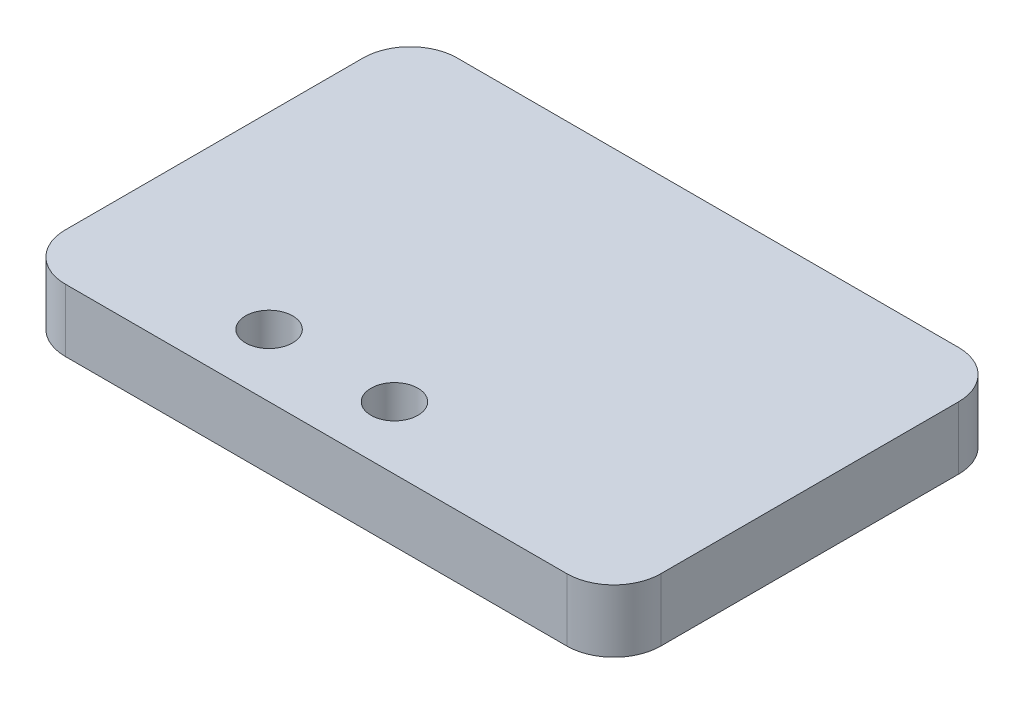
SolidWorks part; units mm, degrees
material "Thornel Mat VMA"
ref_plane "前视基准面" through (0, 0, 0) normal (0, 0, 1) x (1, 0, 0)
ref_plane "上视基准面" through (0, 0, 0) normal (0, 1, 0) x (1, 0, 0)
ref_plane "右视基准面" through (0, 0, 0) normal (1, 0, 0) x (0, 0, -1)
other "Configuration Table"
sketch "草图1" plane through (0, 0, 0) normal (0, 1, 0) x (1, 0, 0)
  line L0 (-19, -8.5) -> (25.3146, -8.5) construction
  line L1 (-19, -12.5) -> (19, -12.5)
  line L2 (-19, -12.5) -> (-19, 12.5)
  line L3 (-19, 12.5) -> (19, 12.5)
  line L4 (19, -12.5) -> (19, 12.5)
  line L5 (-19, -12.5) -> (19, 12.5) construction
  line L6 (-19, 12.5) -> (19, -12.5) construction
  line L7 (0, 0) -> (29.1667, 0) construction
  line L8 (0, 0) -> (0, 24.2444) construction
  circle A0 centre (-7, -8.5) radius 1.5
  circle A1 centre (1, -8.5) radius 1.5
  point P0 (0, 0)
  dimension "D3" = 3
  dimension "D4" = 3
  dimension "D5" = 8
  dimension "D6" = 12
  dimension "D1" = 38
  dimension "D2" = 25
  dimension "D7" = 4
extrude "凸台-拉伸1" add sketch "草图1" along normal blind 4
fillet "圆角1" radius 3 4 edges at (19, 2, -12.5) (19, 2, 12.5) (-19, 2, 12.5) (-19, 2, -12.5)
